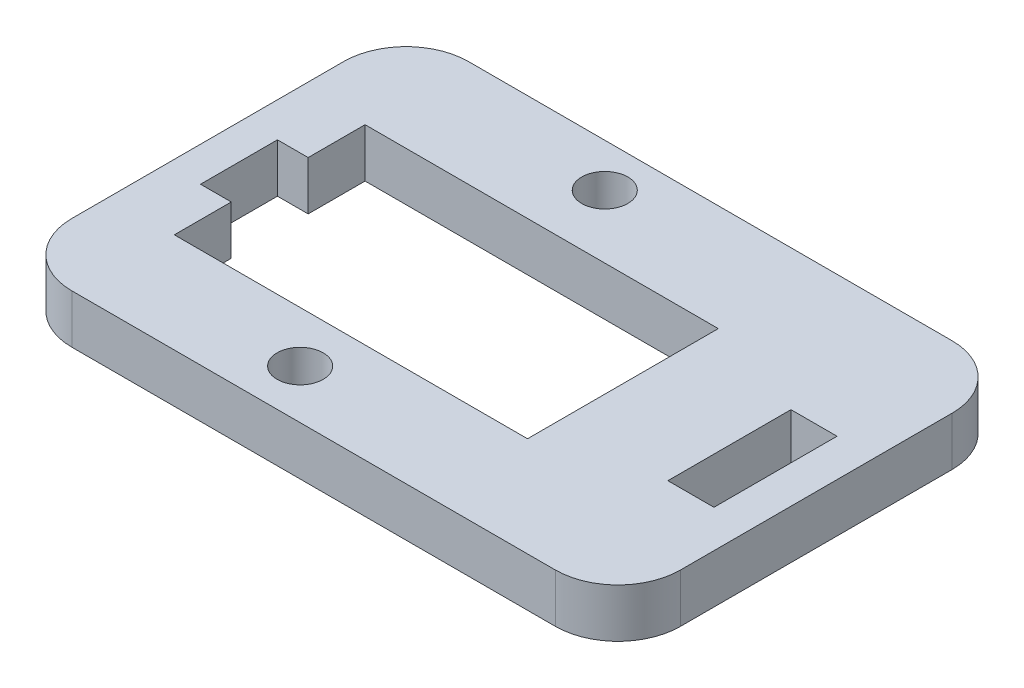
SolidWorks part; units mm, degrees
material "Acrylic (Medium-high impact)"
ref_plane "Front Plane" through (0, 0, 0) normal (0, 0, 1) x (1, 0, 0)
ref_plane "Top Plane" through (0, 0, 0) normal (0, 1, 0) x (1, 0, 0)
ref_plane "Right Plane" through (0, 0, 0) normal (1, 0, 0) x (0, 0, -1)
sketch "Sketch1" plane through (0, 0, 0) normal (0, 1, 0) x (1, 0, 0)
  line L0 (-15.5337, 6.4491) -> (7.4257, 6.4491)
  line L1 (7.4257, 6.4491) -> (7.4257, -5.9515)
  line L2 (7.4257, -5.9515) -> (-15.5337, -5.9515)
  line L3 (-15.5337, -5.9515) -> (-15.5337, -2.2514)
  line L4 (-15.5337, -2.2514) -> (-17.5301, -2.2514)
  line L5 (-17.5301, -2.2514) -> (-17.5301, 2.7488)
  line L6 (-17.5301, 2.7488) -> (-15.5337, 2.7488)
  line L7 (-15.5337, 2.7488) -> (-15.5337, 6.4491)
  line L8 (-15.7247, 13.3647) -> (15.7173, 13.3647)
  line L9 (19.7848, 9.2972) -> (19.7848, -8.3742)
  line L10 (15.7245, -12.4345) -> (-15.7173, -12.4345)
  line L11 (-19.7848, -8.367) -> (-19.7848, 9.3045)
  line L12 (14.3489, 4.2489) -> (17.3436, 4.2489)
  line L13 (17.3436, 4.2489) -> (17.3436, -3.7515)
  line L14 (17.3436, -3.7515) -> (14.3489, -3.7515)
  line L15 (14.3489, -3.7515) -> (14.3489, 4.2489)
  line L16 (-5.5513, 10.5491) -> (-2.5568, 10.5491) construction
  line L17 (-5.5513, -9.2515) -> (-2.5568, -9.2517) construction
  arc A0 (-15.7247, 13.3647) -> (-19.7848, 9.3045) centre (-15.7247, 9.3045) ccw
  arc A1 (-19.7848, -8.367) -> (-15.7173, -12.4345) centre (-15.7173, -8.367) ccw
  arc A2 (15.7245, -12.4345) -> (19.7848, -8.3742) centre (15.7245, -8.3742) ccw
  arc A3 (19.7848, 9.2972) -> (15.7173, 13.3647) centre (15.7173, 9.2972) ccw
  circle A4 centre (-4.0541, 10.5491) radius 1.4973
  circle A5 centre (-4.0541, -9.2516) radius 1.4973
extrude "Boss-Extrude1" add sketch "Sketch1" along normal blind 3.175
